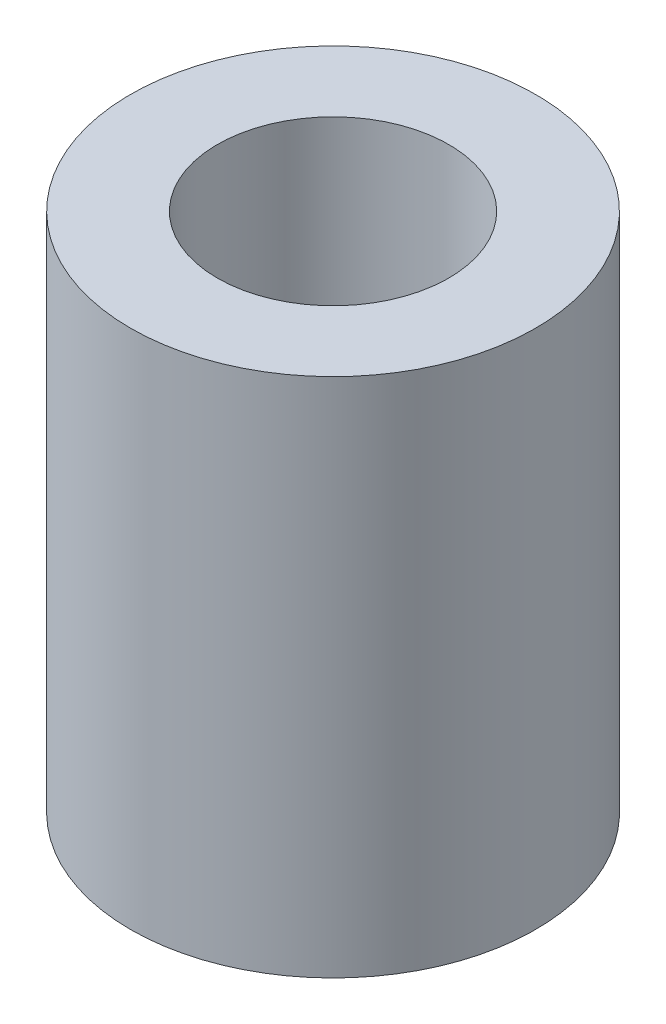
SolidWorks part; units mm, degrees
ref_plane "Front" through (0, 0, 0) normal (0, 0, 1) x (1, 0, 0)
ref_plane "Top" through (0, 0, 0) normal (0, 1, 0) x (1, 0, 0)
ref_plane "Right" through (0, 0, 0) normal (1, 0, 0) x (0, 0, -1)
sketch "Sketch1" plane through (0, 0, 0) normal (0, 1, 0) x (1, 0, 0)
  circle A0 centre (0, 0) radius 2
  circle A1 centre (0, 0) radius 3.5
  dimension "D1" = 4
  dimension "D2" = 1.5
extrude "Boss-Extrude1" add sketch "Sketch1" along normal blind 9
